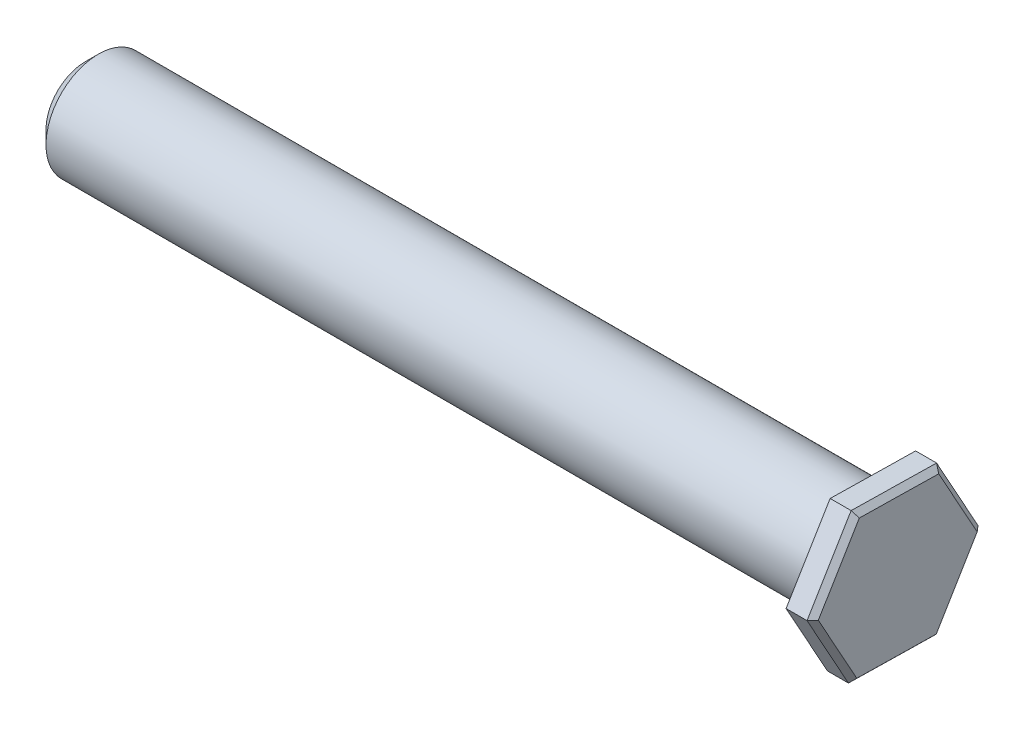
SolidWorks part; units mm, degrees
ref_plane "Front Plane" through (0, 0, 0) normal (0, 0, 1) x (1, 0, 0)
ref_plane "Top Plane" through (0, 0, 0) normal (0, 1, 0) x (1, 0, 0)
ref_plane "Right Plane" through (0, 0, 0) normal (1, 0, 0) x (0, 0, -1)
sketch "Sketch1" plane through (0, 0, 0) normal (1, 0, 0) x (0, 0, -1)
  circle A0 centre (0, 0) radius 10
  dimension "D1" = 20
extrude "Boss-Extrude1" add sketch "Sketch1" along normal blind 150
cosmetic thread "Cosmetic Thread1" parameters "D1"=60, "D2"=6.619
sketch "Sketch2" plane through (150, 0, 0) normal (1, 0, 0) x (0, 0, -1)
  line L1 (-16.3085, 0.2966) -> (-8.4111, -13.9752)
  line L2 (-8.4111, -13.9752) -> (7.8974, -14.2718)
  line L3 (7.8974, -14.2718) -> (16.3085, -0.2966)
  line L4 (16.3085, -0.2966) -> (8.4111, 13.9752)
  line L5 (8.4111, 13.9752) -> (-7.8974, 14.2718)
  line L6 (-7.8974, 14.2718) -> (-16.3085, 0.2966)
  circle A0 centre (0, 0) radius 14.1259 construction
extrude "Boss-Extrude2" add sketch "Sketch2" along normal blind 5
chamfer "Chamfer1" distance 1 angle 45 6 edges at (155, 14.1235, -0.2569) (155, 6.8393, -12.3598) (155, -7.2842, -12.1029) (155, -14.1235, 0.2569) (155, -6.8393, 12.3598) (155, 7.2842, 12.1029)
chamfer "Chamfer3" distance 2.5 angle 45 1 edges at (0, 0, -10)
